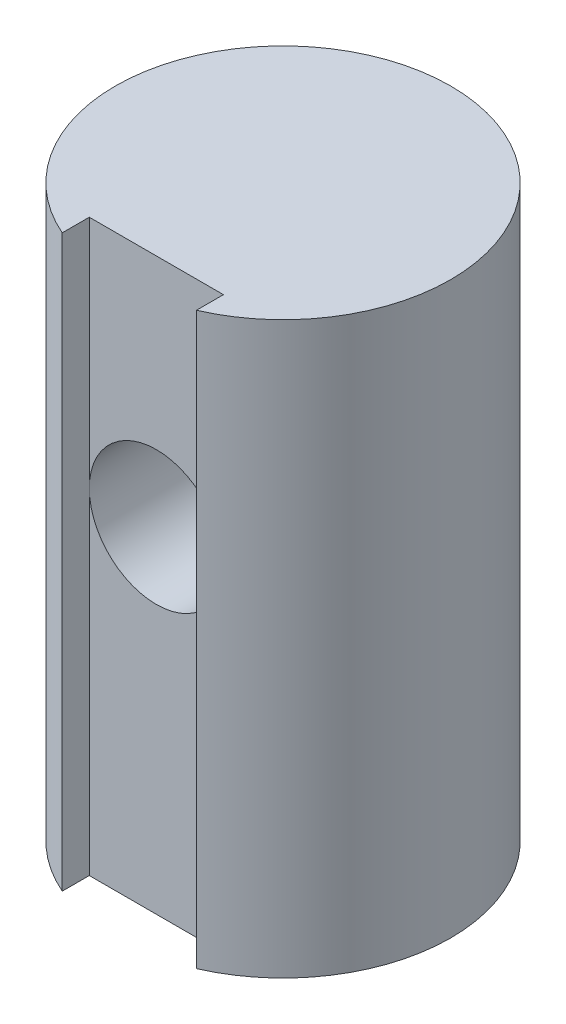
SolidWorks part; units mm, degrees
ref_plane "Front Plane" through (0, 0, 0) normal (0, 0, 1) x (1, 0, 0)
ref_plane "Top Plane" through (0, 0, 0) normal (0, 1, 0) x (1, 0, 0)
ref_plane "Right Plane" through (0, 0, 0) normal (1, 0, 0) x (0, 0, -1)
sketch "Sketch1" plane through (0, 0, 0) normal (0, 1, 0) x (1, 0, 0)
  circle A0 centre (0, 0) radius 15.875
  dimension "flue_block_diameter" = 31.75
extrude "cylinder" add sketch "Sketch1" along normal blind 53.975
sketch "Sketch2" plane through (0, 53.975, 0) normal (0, 1, 0) x (1, 0, 0)
  line L0 (0, -15.875) -> (0, -11.9888) construction
  line L1 (-6.35, -11.9888) -> (6.35, -11.9888)
  line L2 (-6.35, -11.9888) -> (-6.35, -15.875)
  line L3 (-6.35, -15.875) -> (6.35, -15.875)
  line L4 (6.35, -11.9888) -> (6.35, -15.875)
  line L5 (-6.35, -11.9888) -> (6.35, -15.875) construction
  line L6 (-6.35, -15.875) -> (6.35, -11.9888) construction
  line L7 (0, 0) -> (0, -11.9888) construction
  circle A0 centre (0, 0) radius 15.875 construction
  point P0 (0, -13.9319)
  dimension "flue_engagement" = 3.8862
  dimension "flue_width" = 12.7
extrude "flue track" cut sketch "Sketch2" against normal blind 76.2
sketch "Sketch3" plane through (0, 0, 0) normal (0, 0, 1) x (1, 0, 0)
  line L0 (6.35, 53.975) -> (-6.35, 53.975) construction
  line L1 (0, 53.975) -> (0, 31.75) construction
  circle A0 centre (0, 31.75) radius 6.35
  point P5 (0, 38.1)
  dimension "duct_diameter" = 12.7
  dimension "duct_location" = 22.225
extrude "air duct" cut sketch "Sketch3" against normal through all both and the other way through all
